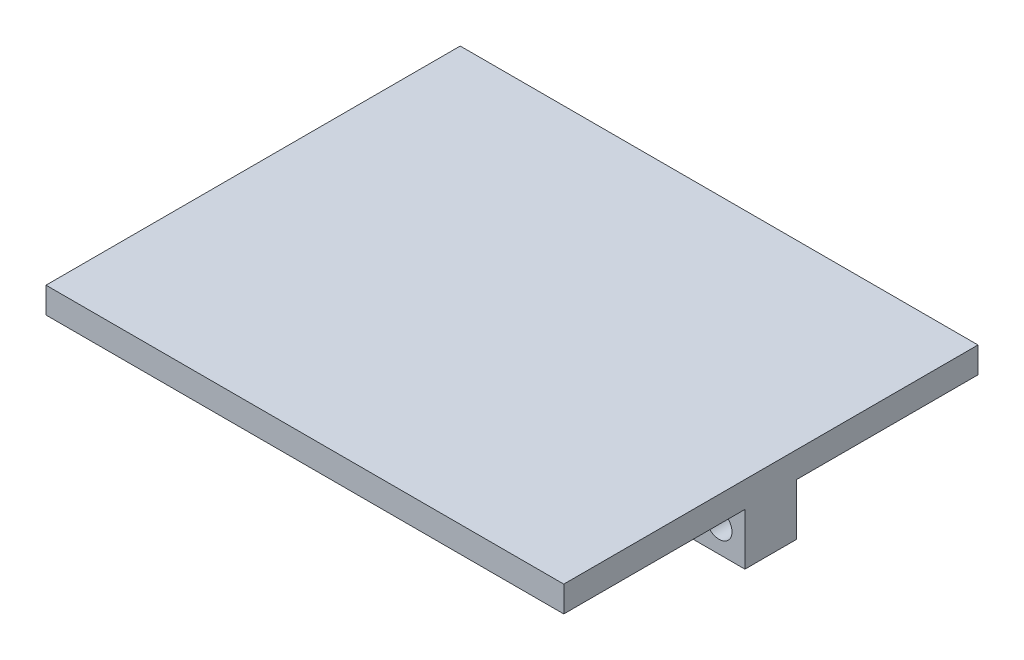
SolidWorks part; units mm, degrees
ref_plane "Front Plane" through (0, 0, 0) normal (0, 0, 1) x (1, 0, 0)
ref_plane "Top Plane" through (0, 0, 0) normal (0, 1, 0) x (1, 0, 0)
ref_plane "Right Plane" through (0, 0, 0) normal (1, 0, 0) x (0, 0, -1)
sketch "Sketch1" plane through (0, 0, 0) normal (0, 1, 0) x (1, 0, 0)
  line L1 (-50, 40) -> (50, 40)
  line L2 (-50, 40) -> (-50, -40)
  line L3 (-50, -40) -> (50, -40)
  line L4 (50, 40) -> (50, -40)
  line L5 (-50, 40) -> (50, -40) construction
  line L6 (-50, -40) -> (50, 40) construction
  point P0 (0, 0)
  dimension "D1" = 100
  dimension "D2" = 80
extrude "Boss-Extrude1" add sketch "Sketch1" along normal mid plane 5
sketch "Sketch2" plane through (0, 2.5, 0) normal (0, 1, 0) x (1, 0, 0)
  line L0 (-50, 40) -> (-50, 20)
  line L1 (-50, 40) -> (-50, -40) construction
  line L2 (-50, 20) -> (50, 20)
  line L3 (50, -40) -> (50, 40) construction
  line L4 (50, 20) -> (50, 10)
  line L5 (50, 10) -> (-50, 10)
  line L6 (-50, 10) -> (-50, 0)
  line L7 (-50, 0) -> (50, 0)
  line L8 (50, 0) -> (50, -10)
  line L9 (50, -10) -> (-50, -10)
  line L10 (-50, -10) -> (-50, -20)
  line L11 (-50, -20) -> (50, -20)
  line L12 (50, -20) -> (50, -40)
  line L13 (50, -40) -> (30, -40)
  line L14 (-50, -40) -> (50, -40) construction
  line L15 (30, -40) -> (30, 40)
  line L16 (50, 40) -> (-50, 40) construction
  line L17 (30, 40) -> (20, 40)
  line L18 (20, 40) -> (20, -40)
  line L19 (20, -40) -> (10, -40)
  line L20 (10, -40) -> (10, 40)
  line L21 (10, 40) -> (0, 40)
  line L22 (0, 40) -> (0, -40)
  line L23 (0, -40) -> (-10, -40)
  line L24 (-10, -40) -> (-10, 40)
  line L25 (-10, 40) -> (-20, 40)
  line L26 (-20, 40) -> (-20, -40)
  line L27 (-20, -40) -> (-30, -40)
  line L28 (-30, -40) -> (-30, 40)
  line L29 (-50, 40) -> (50, 40)
  line L30 (50, 40) -> (50, -40)
  line L31 (-50, -40) -> (-50, 40)
  line L32 (-50, -40) -> (50, -40)
  line L33 (50, -40) -> (50, 40)
  line L34 (-30, 40) -> (-40, 40)
  line L35 (-40, 40) -> (-40, -40)
  line L36 (-40, -40) -> (-50, -40)
  line L37 (-50, -40) -> (-50, -30)
  line L38 (-50, -30) -> (50, -30)
  line L39 (50, -30) -> (50, 30)
  line L40 (50, 30) -> (-50, 30)
  line L41 (50, 40) -> (40, 40)
  line L42 (40, 40) -> (40, -40)
sketch "Sketch3" plane through (0, -2.5, 0) normal (0, -1, 0) x (1, 0, 0)
  line L0 (50, -40) -> (50, 40) construction
  line L2 (-50, 5.0131) -> (-50, -4.9869)
  line L4 (50, 5.0131) -> (50, -4.9869)
  line L8 (50, 5.0131) -> (40, 5.0131)
  line L11 (-50, -4.9869) -> (-40, -4.9869)
  line L12 (40, -4.9869) -> (50, -4.9869)
  line L13 (-50, 40) -> (-50, -40) construction
  line L15 (-40, -40) -> (-40, 40) construction
  line L16 (-40, 5.0131) -> (-50, 5.0131)
  line L17 (-40, 5.0131) -> (-40, -4.9869)
  line L18 (40, 5.0131) -> (40, -4.9869)
  point P0 (0, 0)
  dimension "D1" = 10
  dimension "D2" = 10
  dimension "D3" = 0
extrude "Boss-Extrude2" add sketch "Sketch3" along normal blind 10
sketch "Sketch6" plane through (0, 0, 5.0131) normal (0, 0, 1) x (1, 0, 0)
  circle A0 centre (-45, -7.5) radius 2.5
  circle A1 centre (45, -7.5) radius 2.5
extrude "Cut-Extrude2" cut sketch "Sketch6" against normal blind 10
